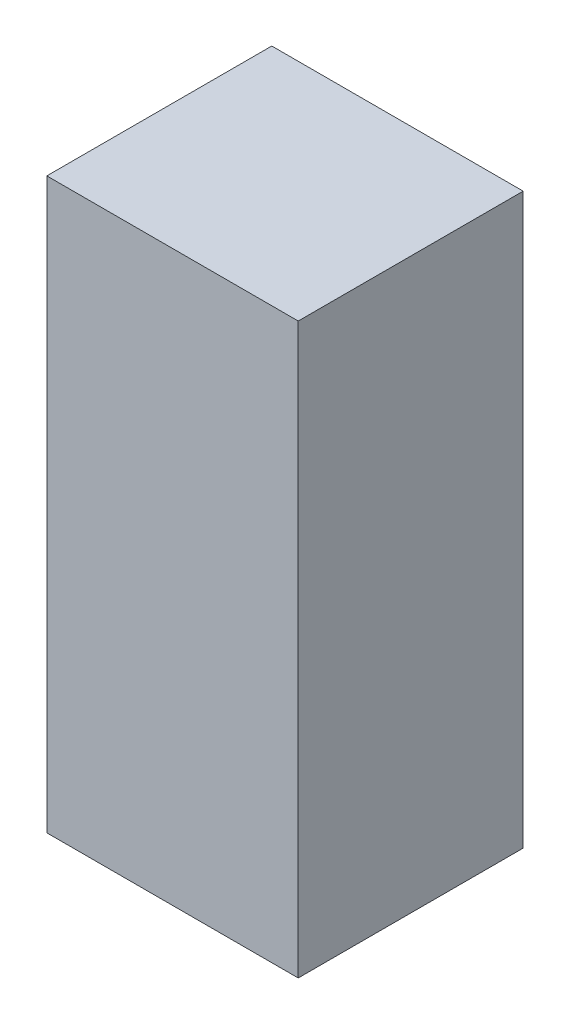
SolidWorks part; units mm, degrees
ref_plane "前视基准面" through (0, 0, 0) normal (0, 0, 1) x (1, 0, 0)
ref_plane "上视基准面" through (0, 0, 0) normal (0, 1, 0) x (1, 0, 0)
ref_plane "右视基准面" through (0, 0, 0) normal (1, 0, 0) x (0, 0, -1)
other "Configuration Table"
sketch "草图1" plane through (0, 0, 0) normal (0, 1, 0) x (1, 0, 0)
  line L1 (9.5, -8.5) -> (-9.5, -8.5)
  line L2 (9.5, -8.5) -> (9.5, 8.5)
  line L3 (9.5, 8.5) -> (-9.5, 8.5)
  line L4 (-9.5, -8.5) -> (-9.5, 8.5)
  line L5 (9.5, -8.5) -> (-9.5, 8.5) construction
  line L6 (9.5, 8.5) -> (-9.5, -8.5) construction
  point P0 (0, 0)
  dimension "D1" = 17
  dimension "D2" = 19
extrude "凸台-拉伸1" add sketch "草图1" along normal blind 43
